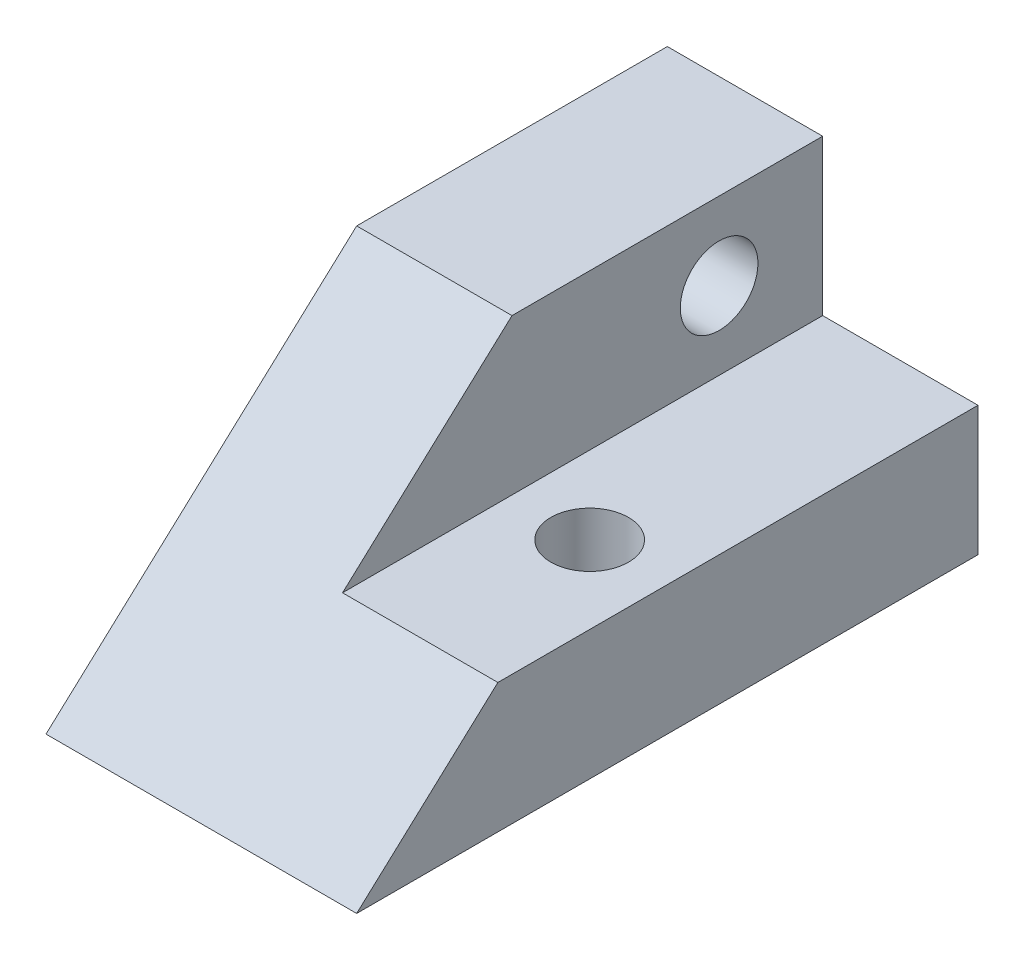
SolidWorks part; units mm, degrees
ref_plane "정면" through (0, 0, 0) normal (0, 0, 1) x (1, 0, 0)
ref_plane "윗면" through (0, 0, 0) normal (0, 1, 0) x (1, 0, 0)
ref_plane "우측면" through (0, 0, 0) normal (1, 0, 0) x (0, 0, -1)
sketch "Sketch1" plane through (0, 0, 0) normal (0, 1, 0) x (1, 0, 0)
  line L1 (-30, 120) -> (30, 120)
  line L2 (-30, 120) -> (-30, 0)
  line L3 (-30, 0) -> (30, 0)
  line L4 (30, 120) -> (30, 0)
  point P4 (0, 0)
  dimension "D1" = 120
  dimension "D2" = 60
extrude "Boss-Extrude1" add sketch "Sketch1" along normal blind 55
sketch "Sketch2" plane through (30, 0, 0) normal (1, 0, 0) x (0, 0, -1)
  line L0 (0, 0) -> (60, 55)
  line L1 (0, 55) -> (120, 55) construction
  line L2 (60, 55) -> (0, 55)
  line L3 (0, 55) -> (0, 0) construction
  line L4 (0, 55) -> (0, 0)
  dimension "D1" = 60
extrude "Cut-Extrude1" cut sketch "Sketch2" against normal through all
sketch "Sketch3" plane through (0, 0, -120) normal (0, 0, -1) x (-1, 0, 0)
  line L0 (-30, 55) -> (30, 55) construction
  line L1 (-30, 55) -> (0, 55)
  line L2 (-30, 55) -> (-30, 25)
  line L3 (-30, 25) -> (0, 25)
  line L4 (0, 55) -> (0, 25)
  dimension "D1" = 30
  dimension "D2" = 30
extrude "Cut-Extrude2" cut sketch "Sketch3" against normal through all contours L4 L3 L2 L1
sketch "Sketch5" plane through (0, 0, 0) normal (1, 0, 0) x (0, 0, -1)
  line L0 (60, 55) -> (120, 55) construction
  line L1 (120, 55) -> (120, 25) construction
  circle A0 centre (100, 40) radius 7.5
  dimension "D1" = 15
  dimension "D2" = 15
  dimension "D3" = 20
extrude "Cut-Extrude3" cut sketch "Sketch5" against normal through all
sketch "Sketch6" plane through (0, 25, 0) normal (0, 1, 0) x (1, 0, 0)
  line L0 (30, 27.2727) -> (30, 120) construction
  line L1 (30, 120) -> (0, 120) construction
  circle A0 centre (15, 60) radius 7.5
  dimension "D2" = 60
  dimension "D3" = 15
  dimension "D1" = 15
extrude "Cut-Extrude4" cut sketch "Sketch6" against normal through all contours A0
